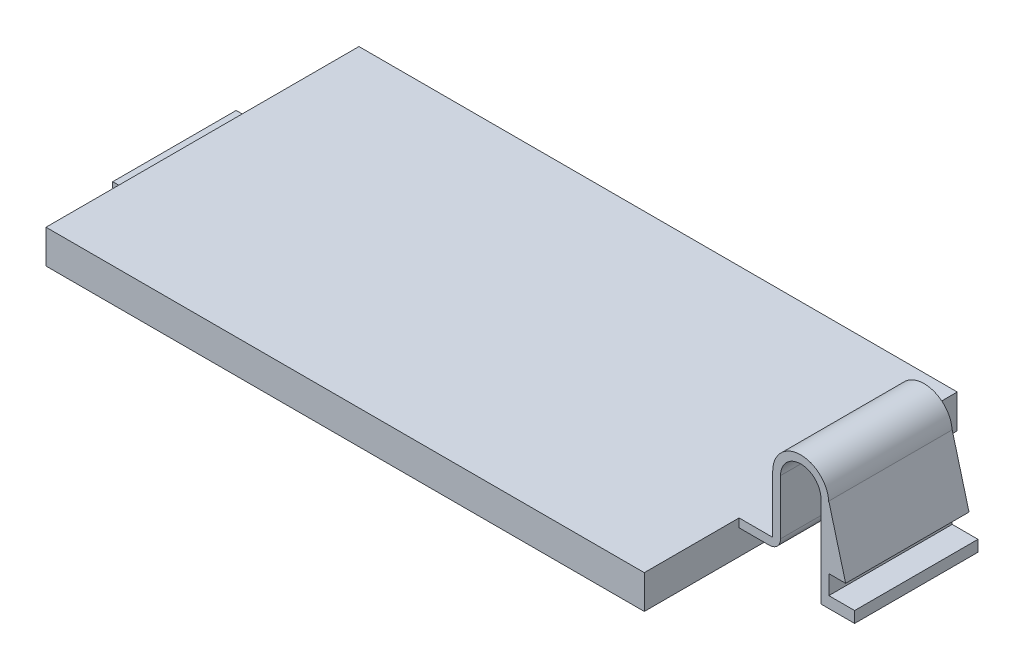
SolidWorks part; units mm, degrees
ref_plane "Front Plane" through (0, 0, 0) normal (0, 0, 1) x (1, 0, 0)
ref_plane "Top Plane" through (0, 0, 0) normal (0, 1, 0) x (1, 0, 0)
ref_plane "Right Plane" through (0, 0, 0) normal (1, 0, 0) x (0, 0, -1)
sketch "Sketch1" plane through (0, 0, 0) normal (0, 0, 1) x (1, 0, 0)
  line L0 (0, 0) -> (2.5, 0)
  line L1 (2.5, 0) -> (2.5, -0.54)
  line L2 (2.5, -0.54) -> (55.84, -0.54)
  line L3 (55.84, -0.54) -> (55.84, 1.698)
  line L4 (55.84, 1.698) -> (57.84, 1.698)
  line L12 (55.84, 2.46) -> (2.5, 2.46)
  line L13 (2.5, 2.46) -> (2.5, 0.5)
  line L14 (2.5, 0.5) -> (0, 0.5)
  line L15 (0, 0.5) -> (0, 0)
  line L16 (55.84, 2.46) -> (58.84, 2.46)
  line L25 (58.54, 1.698) -> (57.84, 1.698)
  line L27 (58.84, 2.46) -> (58.84, 7.579)
  line L28 (59.54, 2.698) -> (59.54, 7.579)
  line L29 (63.84, 7.7581) -> (63.84, 7.579)
  line L34 (63.84, 7.7581) -> (65.34, 2.16)
  line L35 (65.34, 2.16) -> (63.84, 2.16)
  line L41 (63.14, -0.54) -> (63.14, 7.579)
  line L42 (63.84, 0.46) -> (66.14, 0.46)
  line L43 (66.14, 0.46) -> (66.14, -0.54)
  line L44 (66.14, -0.54) -> (63.14, -0.54)
  line L45 (66.14, -0.54) -> (66.14, -0.4875) construction
  line L46 (63.84, 2.16) -> (63.84, 0.46)
  arc A0 (58.84, 7.579) -> (63.84, 7.579) centre (61.34, 7.579) cw
  arc A1 (59.54, 7.579) -> (63.14, 7.579) centre (61.34, 7.579) cw
  arc A4 (59.54, 2.698) -> (58.54, 1.698) centre (58.54, 2.698) cw
  point P12 (61.34, 10.079)
  point P21 (61.34, 9.379)
  point P27 (69.84, -0.0925)
  point P32 (59.54, 1.698)
  dimension "D14" = 0.7
  dimension "D18" = 1.5
  dimension "D19" = 1
  dimension "D1" = 0.54
  dimension "D2" = 2.5
  dimension "D3" = 0.5
  dimension "D4" = 3
  dimension "D5" = 53.34
  dimension "D6" = 53.34
  dimension "D7" = 2.5
  dimension "D8" = 2
  dimension "D9" = 3
  dimension "D10" = 0.762
  dimension "D11" = 1.7
  dimension "D12" = 0.7
  dimension "D13" = 0.7
  dimension "D15" = 1
  dimension "D16" = 8
  dimension "D17" = 3
  dimension "D20" = 15
extrude "Boss-Extrude1" add sketch "Sketch1" along normal mid plane 11
sketch "Sketch2" plane through (0, 0, 0) normal (0, 0, 1) x (1, 0, 0)
  line L0 (2.5, -0.54) -> (55.84, -0.54) construction
  line L1 (58.84, 2.46) -> (2.5, 2.46) construction
  line L2 (2.5, -0.54) -> (55.84, -0.54) construction
  line L3 (58.84, 2.46) -> (2.5, 2.46) construction
  line L5 (2.5, 2.46) -> (55.84, 2.46)
  line L6 (2.5, 2.46) -> (2.5, -0.54)
  line L7 (2.5, -0.54) -> (55.84, -0.54)
  line L8 (55.84, 2.46) -> (55.84, -0.54)
extrude "Boss-Extrude2" add sketch "Sketch2" along normal mid plane 27.9
sketch "Sketch3" plane through (0, 0, 0) normal (0, 0, 1) x (1, 0, 0)
  line L0 (55.84, -0.54) -> (55.84, 2.46) construction
  line L1 (55.84, -0.54) -> (55.84, 2.46) construction
  line L3 (55.84, -0.54) -> (47.84, -0.54)
  line L4 (55.84, -0.54) -> (55.84, 0.36)
  line L5 (55.84, 0.36) -> (47.84, 0.36)
  line L6 (47.84, -0.54) -> (47.84, 0.36)
  dimension "D1" = 8
  dimension "D2" = 0.9
scale "Scale1" bodies to scale 102 scale about centroid uniform scaling yes scale factor 0.98
